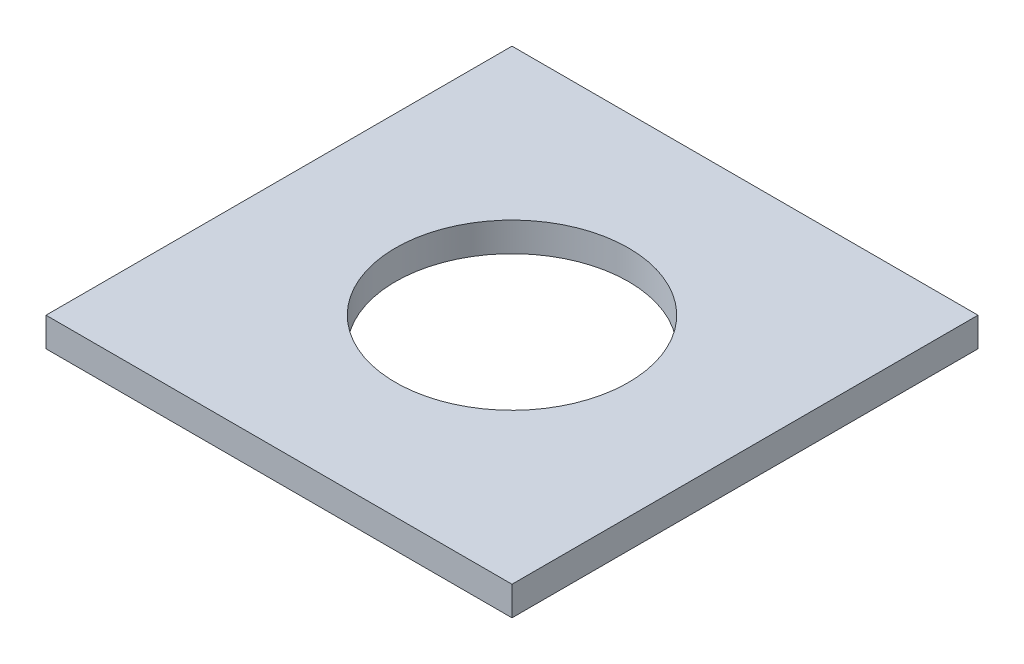
SolidWorks part; units mm, degrees
ref_plane "Front Plane" through (0, 0, 0) normal (0, 0, 1) x (1, 0, 0)
ref_plane "Top Plane" through (0, 0, 0) normal (0, 1, 0) x (1, 0, 0)
ref_plane "Right Plane" through (0, 0, 0) normal (1, 0, 0) x (0, 0, -1)
sketch "Sketch1" plane through (0, 0, 0) normal (0, 1, 0) x (1, 0, 0)
  line L1 (-76.2, -76.2) -> (76.2, -76.2)
  line L2 (-76.2, -76.2) -> (-76.2, 76.2)
  line L3 (-76.2, 76.2) -> (76.2, 76.2)
  line L4 (76.2, -76.2) -> (76.2, 76.2)
  line L5 (-76.2, -76.2) -> (76.2, 76.2) construction
  line L6 (-76.2, 76.2) -> (76.2, -76.2) construction
  circle A0 centre (0, 0) radius 38.1
  point P0 (0, 0)
  dimension "D3" = 76.2
  dimension "D1" = 152.4
  dimension "D2" = 152.4
extrude "Boss-Extrude1" add sketch "Sketch1" along normal blind 9.525
